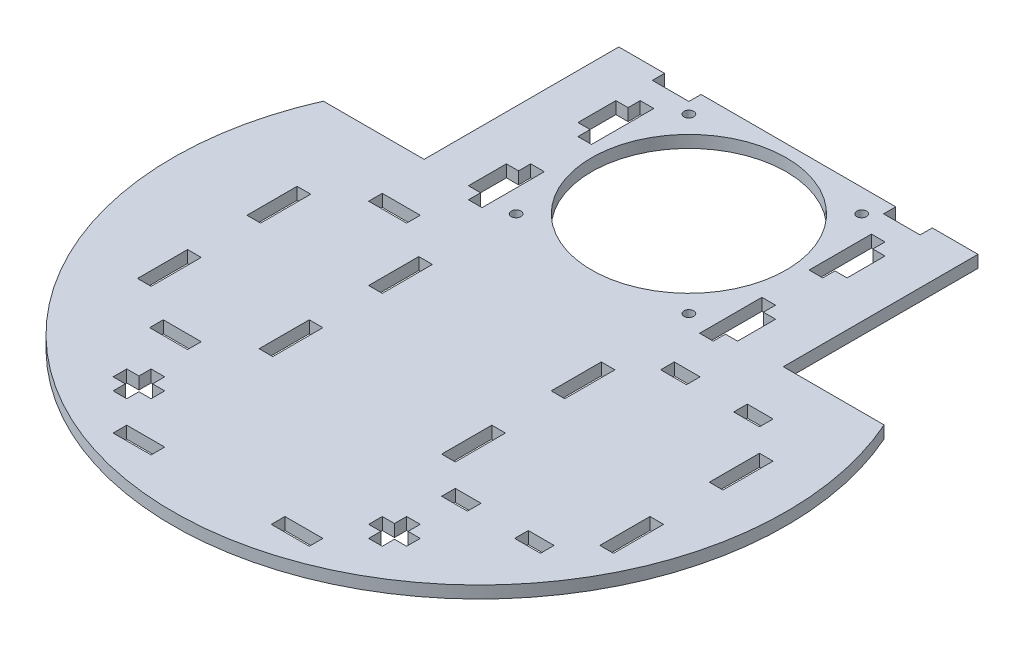
SolidWorks part; units mm, degrees
ref_plane "Front Plane" through (0, 0, 0) normal (0, 0, 1) x (1, 0, 0)
ref_plane "Top Plane" through (0, 0, 0) normal (0, 1, 0) x (1, 0, 0)
ref_plane "Right Plane" through (0, 0, 0) normal (1, 0, 0) x (0, 0, -1)
sketch "Sketch1" plane through (0, 0, 0) normal (0, -1, 0) x (-1, 0, 0)
  line L0 (-70.4767, 28.967) -> (-70.4767, -147.0162) construction
  line L3 (-144.2767, 28.967) -> (-144.2767, -46.033)
  line L5 (-144.2767, -46.033) -> (-185.6939, -46.033)
  line L11 (3.3233, -46.033) -> (44.7405, -46.033)
  line L24 (-95.4767, -122.033) -> (-45.4767, -72.033) construction
  line L25 (-95.4767, -72.033) -> (-45.4767, -122.033) construction
  line L26 (3.3233, 28.967) -> (3.3233, -46.033)
  line L27 (-144.2767, 28.967) -> (-144.2767, 33.967)
  line L28 (-144.2767, 33.967) -> (-125.4767, 33.967)
  line L29 (3.3233, 33.967) -> (3.3233, 28.967)
  line L121 (-15.4767, 28.967) -> (-30.4767, 28.967)
  line L123 (-125.4767, 33.967) -> (-125.4767, 28.967)
  line L124 (-125.4767, 28.967) -> (-110.4767, 28.967)
  line L125 (-110.4767, 33.967) -> (-110.4767, 28.967)
  line L126 (-30.4767, 33.967) -> (-30.4767, 28.967)
  line L128 (-15.4767, 33.967) -> (-15.4767, 28.967)
  line L129 (-110.4767, 33.967) -> (-30.4767, 33.967)
  line L130 (-15.4767, 33.967) -> (3.3233, 33.967)
  line L159 (-20.1767, -6.333) -> (-20.1767, -1.333)
  line L160 (-15.1767, -1.333) -> (-20.1767, -1.333)
  line L161 (-15.1767, 14.267) -> (-15.1767, -1.333)
  line L162 (-15.1767, 14.267) -> (-20.1767, 14.267)
  line L163 (-20.1767, 14.267) -> (-20.1767, 19.267)
  line L164 (-20.1767, 19.267) -> (-25.7767, 19.267)
  line L165 (-25.7767, -6.333) -> (-25.7767, 19.267)
  line L166 (-20.1767, -6.333) -> (-25.7767, -6.333)
  line L167 (-20.1767, -25.733) -> (-20.1767, -30.733)
  line L168 (-15.1767, -30.733) -> (-20.1767, -30.733)
  line L169 (-15.1767, -30.733) -> (-15.1767, -46.333)
  line L170 (-15.1767, -46.333) -> (-20.1767, -46.333)
  line L171 (-20.1767, -46.333) -> (-20.1767, -51.333)
  line L172 (-20.1767, -51.333) -> (-25.7767, -51.333)
  line L173 (-25.7767, -25.733) -> (-25.7767, -51.333)
  line L174 (-20.1767, -25.733) -> (-25.7767, -25.733)
  line L175 (-120.7767, -6.333) -> (-115.1767, -6.333)
  line L176 (-115.1767, -6.333) -> (-115.1767, 19.267)
  line L177 (-120.7767, 19.267) -> (-115.1767, 19.267)
  line L178 (-120.7767, 14.267) -> (-120.7767, 19.267)
  line L179 (-125.7767, 14.267) -> (-120.7767, 14.267)
  line L180 (-125.7767, 14.267) -> (-125.7767, -1.333)
  line L181 (-125.7767, -1.333) -> (-120.7767, -1.333)
  line L182 (-120.7767, -6.333) -> (-120.7767, -1.333)
  line L183 (-120.7767, -25.733) -> (-115.1767, -25.733)
  line L184 (-115.1767, -25.733) -> (-115.1767, -51.333)
  line L185 (-120.7767, -51.333) -> (-115.1767, -51.333)
  line L186 (-120.7767, -46.333) -> (-120.7767, -51.333)
  line L187 (-125.7767, -46.333) -> (-120.7767, -46.333)
  line L188 (-125.7767, -30.733) -> (-125.7767, -46.333)
  line L189 (-125.7767, -30.733) -> (-120.7767, -30.733)
  line L190 (-120.7767, -25.733) -> (-120.7767, -30.733)
  line L191 (-15.7767, -72.333) -> (-15.7767, -66.733)
  line L192 (-15.7767, -66.733) -> (-0.1767, -66.733)
  line L193 (-0.1767, -72.333) -> (-0.1767, -66.733)
  line L194 (-15.7767, -72.333) -> (-0.1767, -72.333)
  line L195 (19.8233, -81.733) -> (19.8233, -102.333)
  line L196 (19.8233, -102.333) -> (14.2233, -102.333)
  line L197 (14.2233, -81.733) -> (14.2233, -102.333)
  line L198 (19.8233, -81.733) -> (14.2233, -81.733)
  line L199 (19.8233, -126.733) -> (19.8233, -147.333)
  line L200 (19.8233, -147.333) -> (14.2233, -147.333)
  line L201 (14.2233, -126.733) -> (14.2233, -147.333)
  line L202 (19.8233, -126.733) -> (14.2233, -126.733)
  line L203 (-15.7767, -162.333) -> (-15.7767, -156.733)
  line L204 (-15.7767, -156.733) -> (-0.1767, -156.733)
  line L205 (-0.1767, -162.333) -> (-0.1767, -156.733)
  line L206 (-15.7767, -162.333) -> (-0.1767, -162.333)
  line L207 (-30.1767, -126.733) -> (-30.1767, -147.333)
  line L208 (-30.1767, -147.333) -> (-35.7767, -147.333)
  line L209 (-35.7767, -126.733) -> (-35.7767, -147.333)
  line L210 (-30.1767, -126.733) -> (-35.7767, -126.733)
  line L211 (-30.1767, -81.733) -> (-30.1767, -102.333)
  line L212 (-30.1767, -102.333) -> (-35.7767, -102.333)
  line L213 (-35.7767, -81.733) -> (-35.7767, -102.333)
  line L214 (-30.1767, -81.733) -> (-35.7767, -81.733)
  line L215 (-30.1767, -207.333) -> (-45.7767, -207.333)
  line L216 (-45.7767, -201.733) -> (-45.7767, -207.333)
  line L217 (-30.1767, -201.733) -> (-45.7767, -201.733)
  line L218 (-30.1767, -201.733) -> (-30.1767, -207.333)
  line L219 (-20.7767, -176.733) -> (-20.7767, -181.733)
  line L220 (-20.7767, -181.733) -> (-25.7767, -181.733)
  line L221 (-25.7767, -181.733) -> (-25.7767, -187.333)
  line L222 (-20.7767, -187.333) -> (-25.7767, -187.333)
  line L223 (-20.7767, -187.333) -> (-20.7767, -192.333)
  line L224 (-20.7767, -192.333) -> (-15.1767, -192.333)
  line L225 (-15.1767, -187.333) -> (-15.1767, -192.333)
  line L226 (-10.1767, -187.333) -> (-15.1767, -187.333)
  line L227 (-10.1767, -181.733) -> (-10.1767, -187.333)
  line L228 (-10.1767, -181.733) -> (-15.1767, -181.733)
  line L229 (-15.1767, -176.733) -> (-15.1767, -181.733)
  line L230 (-20.7767, -176.733) -> (-15.1767, -176.733)
  line L231 (-110.7767, -201.733) -> (-110.7767, -207.333)
  line L232 (-110.7767, -207.333) -> (-95.1767, -207.333)
  line L233 (-95.1767, -201.733) -> (-95.1767, -207.333)
  line L234 (-110.7767, -201.733) -> (-95.1767, -201.733)
  line L235 (-120.1767, -176.733) -> (-125.7767, -176.733)
  line L236 (-125.7767, -176.733) -> (-125.7767, -181.733)
  line L237 (-130.7767, -181.733) -> (-125.7767, -181.733)
  line L238 (-130.7767, -181.733) -> (-130.7767, -187.333)
  line L239 (-130.7767, -187.333) -> (-125.7767, -187.333)
  line L240 (-125.7767, -187.333) -> (-125.7767, -192.333)
  line L241 (-120.1767, -192.333) -> (-125.7767, -192.333)
  line L242 (-120.1767, -187.333) -> (-120.1767, -192.333)
  line L243 (-120.1767, -187.333) -> (-115.1767, -187.333)
  line L244 (-115.1767, -181.733) -> (-115.1767, -187.333)
  line L245 (-120.1767, -181.733) -> (-115.1767, -181.733)
  line L246 (-120.1767, -176.733) -> (-120.1767, -181.733)
  line L247 (-130.7767, -162.333) -> (-130.7767, -156.733)
  line L248 (-130.7767, -156.733) -> (-120.1767, -156.733)
  line L249 (-120.1767, -162.333) -> (-120.1767, -156.733)
  line L250 (-130.7767, -162.333) -> (-120.1767, -162.333)
  line L251 (-160.7767, -162.333) -> (-160.7767, -156.733)
  line L252 (-160.7767, -156.733) -> (-150.1767, -156.733)
  line L253 (-150.1767, -162.333) -> (-150.1767, -156.733)
  line L254 (-160.7767, -162.333) -> (-150.1767, -162.333)
  line L255 (-105.1767, -126.733) -> (-105.1767, -147.333)
  line L256 (-105.1767, -147.333) -> (-110.7767, -147.333)
  line L257 (-110.7767, -126.733) -> (-110.7767, -147.333)
  line L258 (-105.1767, -126.733) -> (-110.7767, -126.733)
  line L259 (-170.1767, -126.733) -> (-170.1767, -147.333)
  line L260 (-170.1767, -147.333) -> (-175.7767, -147.333)
  line L261 (-175.7767, -126.733) -> (-175.7767, -147.333)
  line L262 (-170.1767, -126.733) -> (-175.7767, -126.733)
  line L263 (-170.1767, -81.733) -> (-170.1767, -102.333)
  line L264 (-170.1767, -102.333) -> (-175.7767, -102.333)
  line L265 (-175.7767, -81.733) -> (-175.7767, -102.333)
  line L266 (-170.1767, -81.733) -> (-175.7767, -81.733)
  line L267 (-105.1767, -81.733) -> (-105.1767, -102.333)
  line L268 (-105.1767, -102.333) -> (-110.7767, -102.333)
  line L269 (-110.7767, -81.733) -> (-110.7767, -102.333)
  line L270 (-105.1767, -81.733) -> (-110.7767, -81.733)
  line L271 (-130.7767, -72.333) -> (-130.7767, -66.733)
  line L272 (-130.7767, -66.733) -> (-120.1767, -66.733)
  line L273 (-120.1767, -72.333) -> (-120.1767, -66.733)
  line L274 (-130.7767, -72.333) -> (-120.1767, -72.333)
  line L275 (-160.7767, -72.333) -> (-160.7767, -66.733)
  line L276 (-160.7767, -66.733) -> (-150.1767, -66.733)
  line L277 (-150.1767, -72.333) -> (-150.1767, -66.733)
  line L278 (-160.7767, -72.333) -> (-150.1767, -72.333)
  arc A0 (-185.6939, -46.033) -> (44.7405, -46.033) centre (-70.4767, -97.033) ccw
  circle A1 centre (-70.4767, -11.033) radius 40
  circle A2 centre (-34.9767, 24.467) radius 2
  circle A3 centre (-105.9767, 24.467) radius 2
  circle A4 centre (-105.9767, -46.533) radius 2
  circle A5 centre (-34.9767, -46.533) radius 2
  point P20 (-70.4767, -97.033)
  dimension "D1" = 75
  dimension "D2" = 5
  dimension "D9" = 50
  dimension "D10" = 50
extrude "Boss-Extrude1" add sketch "Sketch1" along normal blind 5
